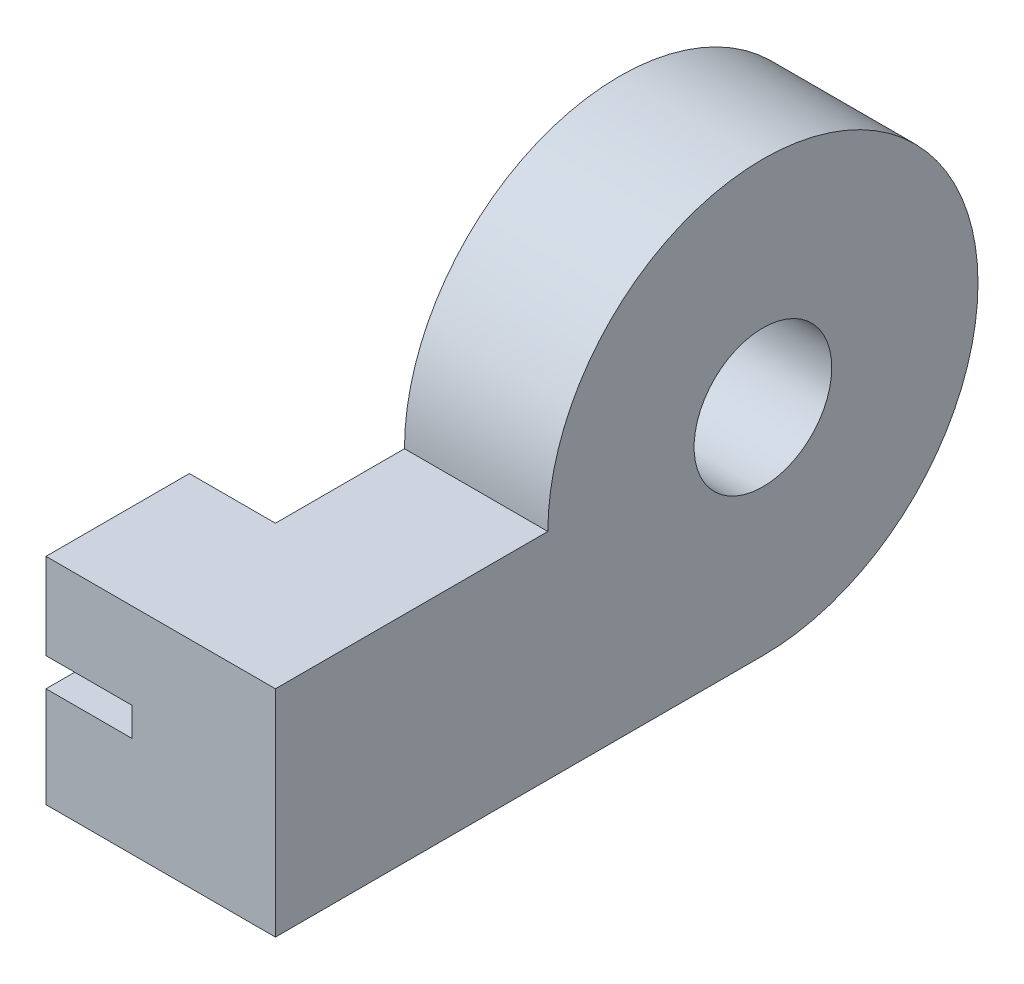
SolidWorks part; units mm, degrees
ref_plane "Front Plane" through (0, 0, 0) normal (0, 0, 1) x (1, 0, 0)
ref_plane "Top Plane" through (0, 0, 0) normal (0, 1, 0) x (1, 0, 0)
ref_plane "Right Plane" through (0, 0, 0) normal (1, 0, 0) x (0, 0, -1)
sketch "Sketch1" plane through (0, 0, 0) normal (1, 0, 0) x (0, 0, -1)
  line L1 (0, -9.525) -> (-21.59, -9.525)
  line L2 (0, -9.525) -> (0, 0)
  line L3 (0, 0) -> (-21.59, 0)
  line L4 (-21.59, -9.525) -> (-21.59, 0)
  circle A0 centre (0, 0) radius 3.048
  circle A1 centre (0, 0) radius 9.525
  point P8 (-21.59, -4.7625)
  dimension "D1" = 6.096
  dimension "D2" = 19.05
  dimension "D3" = 21.59
extrude "Boss-Extrude1" add sketch "Sketch1" along normal blind 6.35 contours L2 A1 L3 A0 | L3 A1 L2 | A1 L3 L4 L1
sketch "Sketch2" plane through (0, 0, 0) normal (-1, 0, 0) x (0, 0, 1)
  line L1 (21.59, 0) -> (15.24, 0)
  line L2 (21.59, 0) -> (21.59, -3.81)
  line L3 (21.59, -3.81) -> (15.24, -3.81)
  line L4 (15.24, 0) -> (15.24, -3.81)
  line L5 (21.59, -9.525) -> (15.24, -9.525)
  line L6 (21.59, -9.525) -> (21.59, -5.08)
  line L7 (21.59, -5.08) -> (15.24, -5.08)
  line L8 (15.24, -9.525) -> (15.24, -5.08)
  dimension "D1" = 4.445
  dimension "D2" = 3.81
  dimension "D3" = 6.35
extrude "Boss-Extrude2" add sketch "Sketch2" along normal blind 3.81 contours L4 L3 L2 L1 | L8 L7 L6 L5
